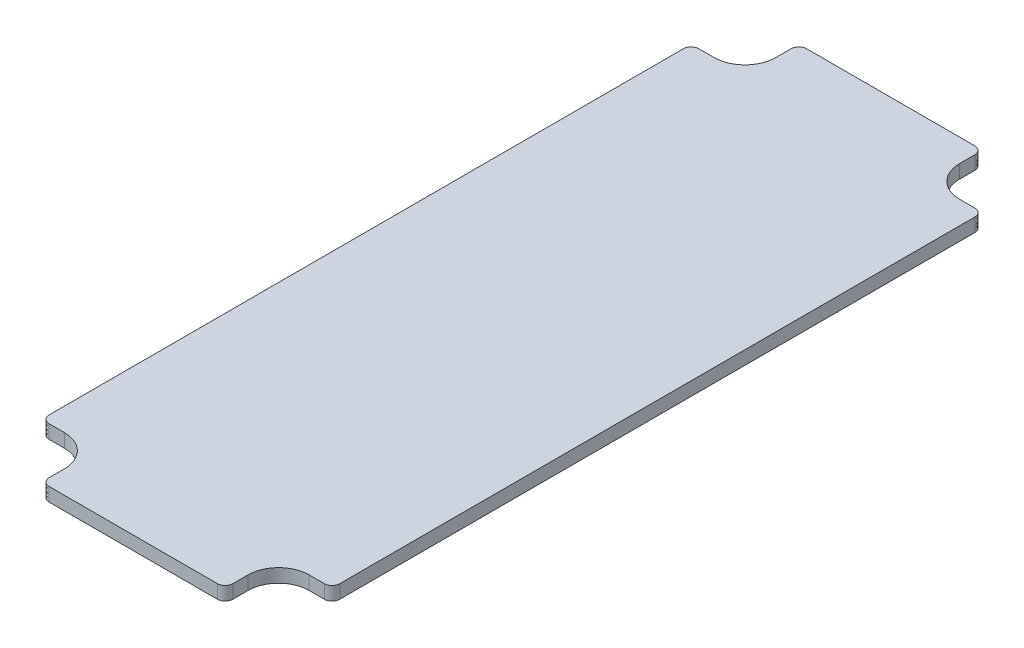
SolidWorks part; units mm, degrees
ref_plane "Front Plane" through (0, 0, 0) normal (0, 0, 1) x (1, 0, 0)
ref_plane "Top Plane" through (0, 0, 0) normal (0, 1, 0) x (1, 0, 0)
ref_plane "Right Plane" through (0, 0, 0) normal (1, 0, 0) x (0, 0, -1)
sketch3d "3DSketch4" plane through (0, 0, 0) normal (0, 0, 1) x (1, 0, 0)
  dimension "D1" = 8
sketch "Sketch2" plane through (0, -15.4498, 0) normal (0, -1, 0) x (-1, 0, 0)
  line L0 (18.7525, 40.3) -> (18.7525, -40.3)
  line L1 (13.25, -45.8025) -> (-13.25, -45.8025)
  line L2 (-13.25, 45.8025) -> (13.25, 45.8025)
  line L3 (-18.7525, -40.3) -> (-18.7525, 40.3)
  line L4 (14.25, 37.8025) -> (16.0028, 37.8025)
  line L5 (-10.7525, 41.3) -> (-10.7525, 43.0528)
  line L6 (-17.0025, -36.8528) -> (-17.0025, 36.8028)
  line L7 (-16.0028, 37.8025) -> (-14.25, 37.8025)
  line L8 (-9.7528, 44.0525) -> (9.7528, 44.0525)
  line L9 (10.7525, 43.0528) -> (10.7525, 41.3)
  line L10 (17.0025, 36.8028) -> (17.0025, -36.7528)
  line L11 (16.0028, -37.7525) -> (14.25, -37.7525)
  line L12 (10.7025, -41.3) -> (10.7025, -43.0528)
  line L13 (9.7028, -44.0525) -> (-9.8028, -44.0525)
  line L14 (-10.8025, -43.0528) -> (-10.8025, -41.3)
  line L15 (-14.25, -37.8525) -> (-16.0028, -37.8525)
  line L16 (-14.25, -37.8525) -> (-16.0028, -37.8525) construction
  line L17 (-10.8025, -43.0528) -> (-10.8025, -41.3) construction
  line L18 (9.7028, -44.0525) -> (-9.8028, -44.0525) construction
  line L19 (10.7025, -41.3) -> (10.7025, -43.0528) construction
  line L20 (16.0028, -37.7525) -> (14.25, -37.7525) construction
  line L21 (17.0025, 36.8028) -> (17.0025, -36.7528) construction
  line L22 (10.7525, 43.0528) -> (10.7525, 41.3) construction
  line L23 (-9.7528, 44.0525) -> (9.7528, 44.0525) construction
  line L24 (-16.0028, 37.8025) -> (-14.25, 37.8025) construction
  line L25 (-17.0025, -36.8528) -> (-17.0025, 36.8028) construction
  line L26 (-10.7525, 41.3) -> (-10.7525, 43.0528) construction
  line L27 (14.25, 37.8025) -> (16.0028, 37.8025) construction
  line L28 (-18.7525, -40.3) -> (-18.7525, 40.3) construction
  line L29 (-13.25, 45.8025) -> (13.25, 45.8025) construction
  line L30 (13.25, -45.8025) -> (-13.25, -45.8025) construction
  line L31 (18.7525, 40.3) -> (18.7525, -40.3) construction
  line L32 (9.7028, -43.9525) -> (-9.8028, -43.9525)
  line L33 (-10.7025, -43.0528) -> (-10.7025, -41.3)
  line L34 (-14.25, -37.7525) -> (-16.0028, -37.7525)
  line L35 (-16.9025, -36.8528) -> (-16.9025, 36.8028)
  line L36 (-16.0028, 37.7025) -> (-14.25, 37.7025)
  line L37 (-10.6525, 41.3) -> (-10.6525, 43.0528)
  line L38 (-9.7528, 43.9525) -> (9.7528, 43.9525)
  line L39 (10.6525, 43.0528) -> (10.6525, 41.3)
  line L40 (14.25, 37.7025) -> (16.0028, 37.7025)
  line L41 (16.9025, 36.8028) -> (16.9025, -36.7528)
  line L42 (16.0028, -37.6525) -> (14.25, -37.6525)
  line L43 (10.6025, -41.3) -> (10.6025, -43.0528)
  arc A0 (13.25, -45.8025) -> (18.7525, -40.3) centre (13.25, -40.3) ccw
  arc A1 (18.7525, 40.3) -> (13.25, 45.8025) centre (13.25, 40.3) ccw
  arc A2 (-13.25, 45.8025) -> (-18.7525, 40.3) centre (-13.25, 40.3) ccw
  arc A3 (-18.7525, -40.3) -> (-13.25, -45.8025) centre (-13.25, -40.3) ccw
  arc A4 (10.7525, 41.3) -> (14.25, 37.8025) centre (14.25, 41.3) ccw
  arc A5 (-14.25, 37.8025) -> (-10.7525, 41.3) centre (-14.25, 41.3) ccw
  arc A6 (14.25, -37.7525) -> (10.7025, -41.3) centre (14.25, -41.3) ccw
  arc A7 (-10.8025, -41.3) -> (-14.25, -37.8525) centre (-14.25, -41.3) ccw
  arc A8 (-10.8025, -41.3) -> (-14.25, -37.8525) centre (-14.25, -41.3) ccw construction
  arc A9 (14.25, -37.7525) -> (10.7025, -41.3) centre (14.25, -41.3) ccw construction
  arc A10 (-14.25, 37.8025) -> (-10.7525, 41.3) centre (-14.25, 41.3) ccw construction
  arc A11 (10.7525, 41.3) -> (14.25, 37.8025) centre (14.25, 41.3) ccw construction
  arc A12 (-18.7525, -40.3) -> (-13.25, -45.8025) centre (-13.25, -40.3) ccw construction
  arc A13 (-13.25, 45.8025) -> (-18.7525, 40.3) centre (-13.25, 40.3) ccw construction
  arc A14 (18.7525, 40.3) -> (13.25, 45.8025) centre (13.25, 40.3) ccw construction
  arc A15 (13.25, -45.8025) -> (18.7525, -40.3) centre (13.25, -40.3) ccw construction
  arc A16 (-10.7025, -41.3) -> (-14.25, -37.7525) centre (-14.25, -41.3) ccw
  arc A17 (-14.25, 37.7025) -> (-10.6525, 41.3) centre (-14.25, 41.3) ccw
  arc A18 (10.6525, 41.3) -> (14.25, 37.7025) centre (14.25, 41.3) ccw
  arc A19 (14.25, -37.6525) -> (10.6025, -41.3) centre (14.25, -41.3) ccw
  spline S0 degree 3 poles (-17.0025, 36.8028) (-17.0025, 37.3885) (-16.5885, 37.8025) (-16.0028, 37.8025) knots 0 0 0 0 1 1 1 1 weights 1 0.804899 0.804899 1
  spline S1 degree 3 poles (-10.7525, 43.0528) (-10.7525, 43.6385) (-10.3385, 44.0525) (-9.7528, 44.0525) knots 0 0 0 0 1 1 1 1 weights 1 0.804899 0.804899 1
  spline S2 degree 3 poles (9.7528, 44.0525) (10.3385, 44.0525) (10.7525, 43.6385) (10.7525, 43.0528) knots 0 0 0 0 1 1 1 1 weights 1 0.804899 0.804899 1
  spline S3 degree 3 poles (16.0028, 37.8025) (16.5885, 37.8025) (17.0025, 37.3885) (17.0025, 36.8028) knots 0 0 0 0 1 1 1 1 weights 1 0.804899 0.804899 1
  spline S4 degree 3 poles (17.0025, -36.7528) (17.0025, -37.3385) (16.5885, -37.7525) (16.0028, -37.7525) knots 0 0 0 0 1 1 1 1 weights 1 0.804899 0.804899 1
  spline S5 degree 3 poles (10.7025, -43.0528) (10.7025, -43.6385) (10.2885, -44.0525) (9.7028, -44.0525) knots 0 0 0 0 1 1 1 1 weights 1 0.804899 0.804899 1
  spline S6 degree 3 poles (-9.8028, -44.0525) (-10.3885, -44.0525) (-10.8025, -43.6385) (-10.8025, -43.0528) knots 0 0 0 0 1 1 1 1 weights 1 0.804899 0.804899 1
  spline S7 degree 3 poles (-16.0028, -37.8525) (-16.5885, -37.8525) (-17.0025, -37.4385) (-17.0025, -36.8528) knots 0 0 0 0 1 1 1 1 weights 1 0.804899 0.804899 1
  spline S8 degree 3 poles (-16.0028, -37.8525) (-16.5885, -37.8525) (-17.0025, -37.4385) (-17.0025, -36.8528) knots 0 0 0 0 1 1 1 1 weights 1 0.804899 0.804899 1 construction
  spline S9 degree 3 poles (-9.8028, -44.0525) (-10.3885, -44.0525) (-10.8025, -43.6385) (-10.8025, -43.0528) knots 0 0 0 0 1 1 1 1 weights 1 0.804899 0.804899 1 construction
  spline S10 degree 3 poles (10.7025, -43.0528) (10.7025, -43.6385) (10.2885, -44.0525) (9.7028, -44.0525) knots 0 0 0 0 1 1 1 1 weights 1 0.804899 0.804899 1 construction
  spline S11 degree 3 poles (17.0025, -36.7528) (17.0025, -37.3385) (16.5885, -37.7525) (16.0028, -37.7525) knots 0 0 0 0 1 1 1 1 weights 1 0.804899 0.804899 1 construction
  spline S12 degree 3 poles (16.0028, 37.8025) (16.5885, 37.8025) (17.0025, 37.3885) (17.0025, 36.8028) knots 0 0 0 0 1 1 1 1 weights 1 0.804899 0.804899 1 construction
  spline S13 degree 3 poles (9.7528, 44.0525) (10.3385, 44.0525) (10.7525, 43.6385) (10.7525, 43.0528) knots 0 0 0 0 1 1 1 1 weights 1 0.804899 0.804899 1 construction
  spline S14 degree 3 poles (-10.7525, 43.0528) (-10.7525, 43.6385) (-10.3385, 44.0525) (-9.7528, 44.0525) knots 0 0 0 0 1 1 1 1 weights 1 0.804899 0.804899 1 construction
  spline S15 degree 3 poles (-17.0025, 36.8028) (-17.0025, 37.3885) (-16.5885, 37.8025) (-16.0028, 37.8025) knots 0 0 0 0 1 1 1 1 weights 1 0.804899 0.804899 1 construction
  spline S16 degree 1 poles (-9.8028, -43.9525) (-10.7025, -43.0528) knots 0 0 1 1 construction
  spline S17 degree 1 poles (-16.0028, -37.7525) (-16.9025, -36.8528) knots 0 0 1 1 construction
  spline S18 degree 1 poles (-16.9025, 36.8028) (-16.0028, 37.7025) knots 0 0 1 1 construction
  spline S19 degree 1 poles (-10.6525, 43.0528) (-9.7528, 43.9525) knots 0 0 1 1 construction
  spline S20 degree 1 poles (9.7528, 43.9525) (10.6525, 43.0528) knots 0 0 1 1 construction
  spline S21 degree 1 poles (16.0028, 37.7025) (16.9025, 36.8028) knots 0 0 1 1 construction
  spline S22 degree 1 poles (16.9025, -36.7528) (16.0028, -37.6525) knots 0 0 1 1 construction
  spline S23 degree 1 poles (10.6025, -43.0528) (9.7028, -43.9525) knots 0 0 1 1 construction
  spline S24 degree 3 poles (-9.8028, -43.9525) (-9.9152, -43.9525) (-10.135, -43.9138) (-10.4588, -43.7088) (-10.6638, -43.385) (-10.7025, -43.1652) (-10.7025, -43.0528) knots 0 0 0 0 0.25 0.5 0.75 1 1 1 1
  spline S25 degree 3 poles (-16.0028, -37.7525) (-16.1152, -37.7525) (-16.335, -37.7138) (-16.6588, -37.5088) (-16.8638, -37.185) (-16.9025, -36.9652) (-16.9025, -36.8528) knots 0 0 0 0 0.25 0.5 0.75 1 1 1 1
  spline S26 degree 3 poles (-16.9025, 36.8028) (-16.9025, 36.9152) (-16.8638, 37.135) (-16.6588, 37.4588) (-16.335, 37.6638) (-16.1152, 37.7025) (-16.0028, 37.7025) knots 0 0 0 0 0.25 0.5 0.75 1 1 1 1
  spline S27 degree 3 poles (-10.6525, 43.0528) (-10.6525, 43.1652) (-10.6138, 43.385) (-10.4088, 43.7088) (-10.085, 43.9138) (-9.8652, 43.9525) (-9.7528, 43.9525) knots 0 0 0 0 0.25 0.5 0.75 1 1 1 1
  spline S28 degree 3 poles (9.7528, 43.9525) (9.8652, 43.9525) (10.085, 43.9138) (10.4088, 43.7088) (10.6138, 43.385) (10.6525, 43.1652) (10.6525, 43.0528) knots 0 0 0 0 0.25 0.5 0.75 1 1 1 1
  spline S29 degree 3 poles (16.0028, 37.7025) (16.1152, 37.7025) (16.335, 37.6638) (16.6588, 37.4588) (16.8638, 37.135) (16.9025, 36.9152) (16.9025, 36.8028) knots 0 0 0 0 0.25 0.5 0.75 1 1 1 1
  spline S30 degree 3 poles (16.9025, -36.7528) (16.9025, -36.8652) (16.8638, -37.085) (16.6588, -37.4088) (16.335, -37.6138) (16.1152, -37.6525) (16.0028, -37.6525) knots 0 0 0 0 0.25 0.5 0.75 1 1 1 1
  spline S31 degree 3 poles (10.6025, -43.0528) (10.6025, -43.1652) (10.5638, -43.385) (10.3588, -43.7088) (10.035, -43.9138) (9.8152, -43.9525) (9.7028, -43.9525) knots 0 0 0 0 0.25 0.5 0.75 1 1 1 1
  dimension "D1" = 0.1
extrude "EffectsBoard" add sketch "Sketch2" against normal blind 1.57
